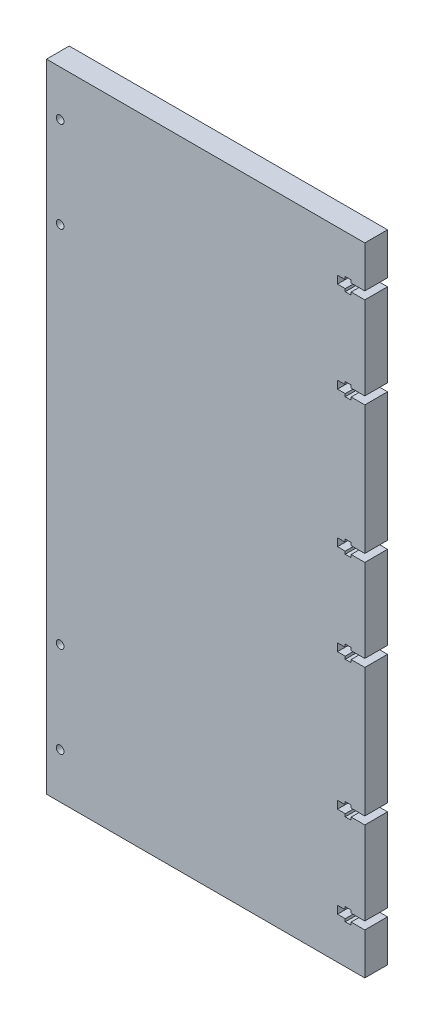
SolidWorks part; units mm, degrees
ref_plane "Front Plane" through (0, 0, 0) normal (0, 0, 1) x (1, 0, 0)
ref_plane "Top Plane" through (0, 0, 0) normal (0, 1, 0) x (1, 0, 0)
ref_plane "Right Plane" through (0, 0, 0) normal (1, 0, 0) x (0, 0, -1)
sketch "Sketch1" plane through (0, 0, 0) normal (0, 0, 1) x (1, 0, 0)
  line L1 (0, 0) -> (177.8, 0)
  line L2 (0, 0) -> (0, 355.6)
  line L3 (0, 355.6) -> (177.8, 355.6)
  line L4 (177.8, 0) -> (177.8, 355.6)
  dimension "D1" = 177.8
  dimension "D2" = 355.6
extrude "Boss-Extrude1" add sketch "Sketch1" along normal blind 12.7
sketch "Sketch3" plane through (0, 0, 12.7) normal (0, 0, 1) x (1, 0, 0)
  line L0 (0, 355.6) -> (0, 0) construction
  line L1 (177.8, 355.6) -> (0, 355.6) construction
  line L2 (0, 177.8) -> (177.8, 177.8) construction
  line L3 (177.8, 0) -> (177.8, 355.6) construction
  line L4 (88.9, 355.6) -> (88.9, 0) construction
  line L5 (0, 0) -> (177.8, 0) construction
  line L6 (177.8, 332.359) -> (170.18, 332.359)
  line L7 (170.18, 332.359) -> (170.18, 333.883)
  line L8 (170.18, 333.883) -> (166.878, 333.883)
  line L9 (166.878, 333.883) -> (166.878, 332.359)
  line L10 (166.878, 332.359) -> (162.56, 332.359)
  line L11 (162.56, 332.359) -> (162.56, 328.041)
  line L12 (162.56, 328.041) -> (166.878, 328.041)
  line L13 (166.878, 328.041) -> (166.878, 326.517)
  line L14 (166.878, 326.517) -> (170.18, 326.517)
  line L15 (170.18, 326.517) -> (170.18, 328.041)
  line L16 (170.18, 328.041) -> (177.8, 328.041)
  line L17 (177.8, 328.041) -> (177.8, 332.359)
  line L18 (0, 304.8) -> (177.8, 304.8) construction
  line L19 (177.8, 281.559) -> (177.8, 277.241)
  line L20 (170.18, 281.559) -> (177.8, 281.559)
  line L21 (170.18, 283.083) -> (170.18, 281.559)
  line L22 (166.878, 283.083) -> (170.18, 283.083)
  line L23 (166.878, 281.559) -> (166.878, 283.083)
  line L24 (162.56, 281.559) -> (166.878, 281.559)
  line L25 (162.56, 277.241) -> (162.56, 281.559)
  line L26 (166.878, 277.241) -> (162.56, 277.241)
  line L27 (166.878, 275.717) -> (166.878, 277.241)
  line L28 (170.18, 275.717) -> (166.878, 275.717)
  line L29 (170.18, 277.241) -> (170.18, 275.717)
  line L30 (177.8, 277.241) -> (170.18, 277.241)
  line L31 (0, 241.3) -> (177.8, 241.3) construction
  line L32 (177.8, 78.359) -> (170.18, 78.359)
  line L33 (170.18, 78.359) -> (170.18, 79.883)
  line L34 (170.18, 79.883) -> (166.878, 79.883)
  line L35 (166.878, 79.883) -> (166.878, 78.359)
  line L36 (166.878, 78.359) -> (162.56, 78.359)
  line L37 (162.56, 78.359) -> (162.56, 74.041)
  line L38 (162.56, 74.041) -> (166.878, 74.041)
  line L39 (166.878, 74.041) -> (166.878, 72.517)
  line L40 (166.878, 72.517) -> (170.18, 72.517)
  line L41 (170.18, 72.517) -> (170.18, 74.041)
  line L42 (170.18, 74.041) -> (177.8, 74.041)
  line L43 (177.8, 74.041) -> (177.8, 78.359)
  line L44 (177.8, 27.559) -> (177.8, 23.241)
  line L45 (170.18, 27.559) -> (177.8, 27.559)
  line L46 (170.18, 29.083) -> (170.18, 27.559)
  line L47 (166.878, 29.083) -> (170.18, 29.083)
  line L48 (166.878, 27.559) -> (166.878, 29.083)
  line L49 (162.56, 27.559) -> (166.878, 27.559)
  line L50 (162.56, 23.241) -> (162.56, 27.559)
  line L51 (166.878, 23.241) -> (162.56, 23.241)
  line L52 (166.878, 21.717) -> (166.878, 23.241)
  line L53 (170.18, 21.717) -> (166.878, 21.717)
  line L54 (170.18, 23.241) -> (170.18, 21.717)
  line L55 (177.8, 23.241) -> (170.18, 23.241)
  line L56 (177.8, 205.359) -> (170.18, 205.359)
  line L57 (170.18, 205.359) -> (170.18, 206.883)
  line L58 (170.18, 206.883) -> (166.878, 206.883)
  line L59 (166.878, 206.883) -> (166.878, 205.359)
  line L60 (166.878, 205.359) -> (162.56, 205.359)
  line L61 (162.56, 205.359) -> (162.56, 201.041)
  line L62 (162.56, 201.041) -> (166.878, 201.041)
  line L63 (166.878, 201.041) -> (166.878, 199.517)
  line L64 (166.878, 199.517) -> (170.18, 199.517)
  line L65 (170.18, 199.517) -> (170.18, 201.041)
  line L66 (170.18, 201.041) -> (177.8, 201.041)
  line L67 (177.8, 201.041) -> (177.8, 205.359)
  line L68 (177.8, 154.559) -> (177.8, 150.241)
  line L69 (170.18, 154.559) -> (177.8, 154.559)
  line L70 (170.18, 156.083) -> (170.18, 154.559)
  line L71 (166.878, 156.083) -> (170.18, 156.083)
  line L72 (166.878, 154.559) -> (166.878, 156.083)
  line L73 (162.56, 154.559) -> (166.878, 154.559)
  line L74 (162.56, 150.241) -> (162.56, 154.559)
  line L75 (166.878, 150.241) -> (162.56, 150.241)
  line L76 (166.878, 148.717) -> (166.878, 150.241)
  line L77 (170.18, 148.717) -> (166.878, 148.717)
  line L78 (170.18, 150.241) -> (170.18, 148.717)
  line L79 (177.8, 150.241) -> (170.18, 150.241)
  circle A0 centre (7.62, 330.2) radius 2.159
  circle A1 centre (7.62, 279.4) radius 2.159
  circle A2 centre (7.62, 76.2) radius 2.159
  circle A3 centre (7.62, 25.4) radius 2.159
  point P34 (177.8, 330.2)
  point P47 (177.8, 279.4)
  point P74 (177.8, 76.2)
  point P75 (177.8, 25.4)
  point P100 (177.8, 203.2)
  point P101 (177.8, 152.4)
  dimension "D1" = 4.318
  dimension "D2" = 7.62
  dimension "D3" = 25.4
  dimension "D4" = 50.8
  dimension "D5" = 25.4
  dimension "D6" = 4.318
  dimension "D7" = 7.62
  dimension "D8" = 3.302
  dimension "D9" = 15.24
  dimension "D10" = 7.366
  dimension "D11" = 25.4
  dimension "D12" = 63.5
extrude "Cut-Extrude1" cut sketch "Sketch3" against normal through all
